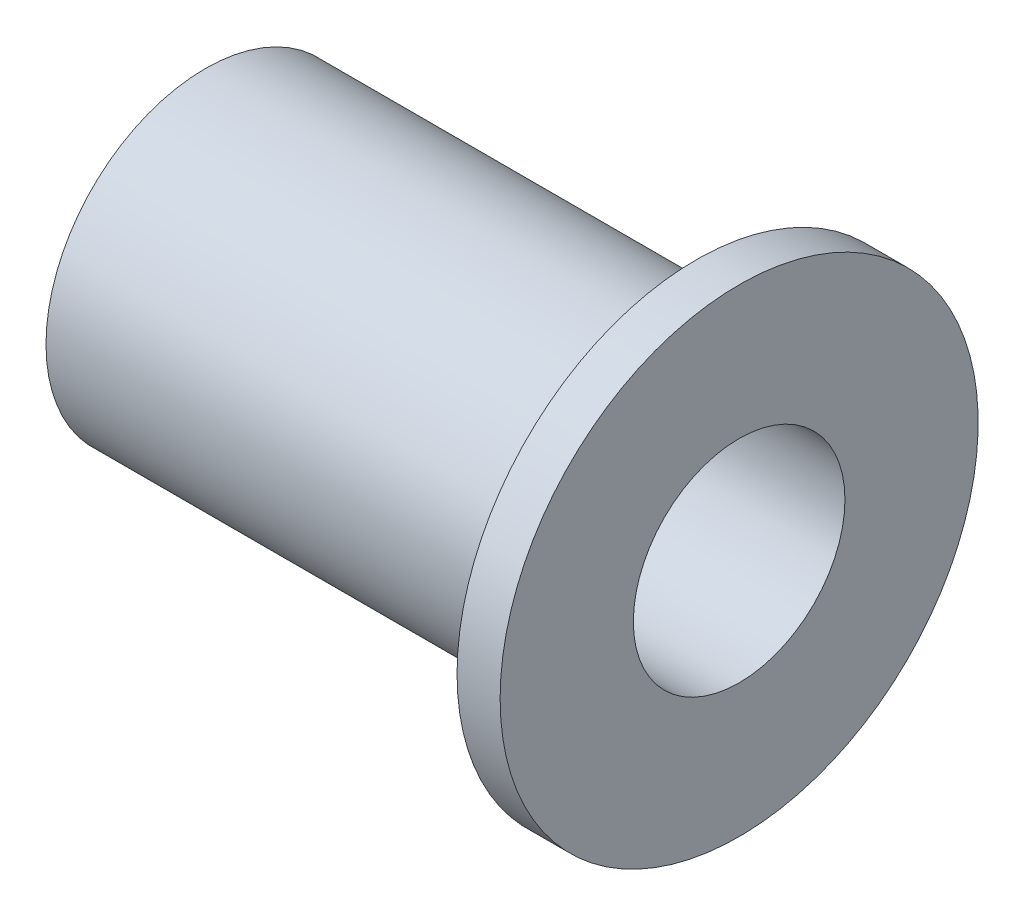
SolidWorks part; units mm, degrees
ref_plane "Piano frontale" through (0, 0, 0) normal (0, 0, 1) x (1, 0, 0)
ref_plane "Piano superiore" through (0, 0, 0) normal (0, 1, 0) x (1, 0, 0)
ref_plane "Piano destro" through (0, 0, 0) normal (1, 0, 0) x (0, 0, -1)
sketch "Schizzo1" plane through (0, 0, 0) normal (0, 0, 1) x (1, 0, 0)
  line L0 (0, 0) -> (10.0716, 0) construction
  line L1 (0, -1.99) -> (0, -2.995)
  line L2 (0, -2.995) -> (9.23, -2.995)
  line L3 (9.23, -2.995) -> (9.23, -4.495)
  line L4 (9.23, -4.495) -> (10.04, -4.495)
  line L5 (10.04, -4.495) -> (10.04, -1.99)
  line L6 (10.04, -1.99) -> (0, -1.99)
  dimension "D1" = 10.04
  dimension "D2" = 0.81
  dimension "D3" = 5.99
  dimension "D4" = 8.99
  dimension "D5" = 3.98
revolve "Rivoluzione1" add sketch "Schizzo1" angle 360 about L0
